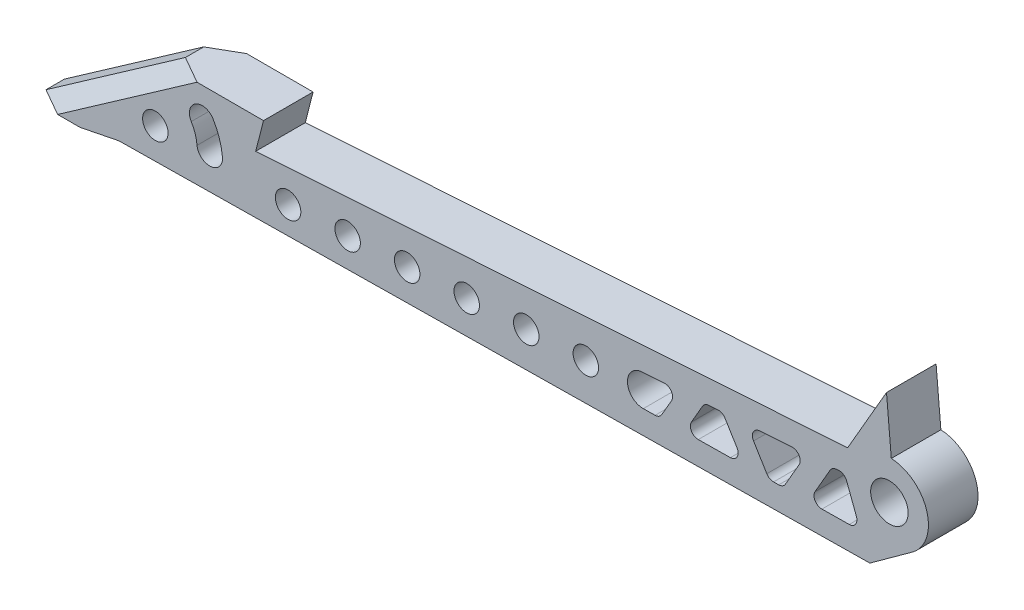
SolidWorks part; units mm, degrees
ref_plane "Front Plane" through (0, 0, 0) normal (0, 0, 1) x (1, 0, 0)
ref_plane "Top Plane" through (0, 0, 0) normal (0, 1, 0) x (1, 0, 0)
ref_plane "Right Plane" through (0, 0, 0) normal (1, 0, 0) x (0, 0, -1)
sketch "Sketch1" plane through (0, 0, 0) normal (0, 0, 1) x (1, 0, 0)
  line L0 (-207.3, -20.475) -> (-197.3, -18.475)
  line L1 (-207.3, -20.475) -> (-220, -20.475)
  line L2 (-220, -20.475) -> (-184.2963, 4.525)
  line L3 (-184.2963, 4.525) -> (-160.2963, 4.525)
  line L4 (-160.2963, 4.525) -> (-162.2963, -3.2821)
  line L5 (-63.3489, -2.738) -> (-11.4925, 0.6985)
  line L6 (-197.3, -18.475) -> (-5, -15.975)
  line L7 (-5, -15.975) -> (5.8689, -8.0967)
  line L8 (-7.1414, 7) -> (-162.2963, -3.2821)
  line L9 (-10.6917, 6.7647) -> (-0.7409, 24)
  line L10 (-11.4925, 0.6985) -> (-7.438, -10.0062)
  line L11 (-7.438, -10.0062) -> (-63.0324, -10.7289)
  line L12 (-0.7409, 24) -> (0.4849, 9.9882)
  line L13 (-0.4809, 25.4503) -> (7.4574, 39.2) construction
  line L14 (-154, -10.975) -> (-138.75, -10.2628)
  line L15 (-154, -17.9121) -> (-154, -2.7323) construction
  line L16 (-138.75, -10.2628) -> (-123.5, -9.5507)
  line L17 (-123.5, -9.5507) -> (-108.25, -8.8385)
  line L18 (-108.25, -8.8385) -> (-93, -8.1263)
  line L19 (-138.75, -10.2628) -> (-123.5, -9.5507)
  line L20 (-123.5, -9.5507) -> (-108.25, -8.8385)
  line L21 (-108.25, -8.8385) -> (-93, -8.1263)
  line L22 (-93, -8.1263) -> (-77.75, -7.4142)
  line L23 (-220, -20.475) -> (248.3161, -20.475) construction
  circle A0 centre (0, 0) radius 10
  circle A1 centre (0, 0) radius 4.8025
  arc A2 (-63.0324, -10.7289) -> (-63.3489, -2.738) centre (-63.0844, -6.7293) cw
  circle A3 centre (-154, -10.975) radius 3.2639
  circle A4 centre (-123.5, -9.5507) radius 3.2639
  circle A5 centre (-93, -8.1263) radius 3.2639
  circle A6 centre (-138.75, -10.2628) radius 3.2639
  circle A7 centre (-108.25, -8.8385) radius 3.2639
  circle A8 centre (-77.75, -7.4142) radius 3.2639
  point P0 (0, 0)
  point P3 (-180.2963, -4.475)
  point P42 (-172.5511, -3.4613)
  point P43 (-171.7203, -3.4613)
  point P44 (-170.2963, -3.8123)
  point P45 (0, 0)
  point P46 (-190, -11.126)
  dimension "D17" = 4
  dimension "D18" = 6.5278
  dimension "D8" = 20
  dimension "D22" = 9.605
  dimension "D1" = 12.7
  dimension "D2" = 35
  dimension "D3" = 220
  dimension "D4" = 24
  dimension "D5" = 2
  dimension "D6" = 25
  dimension "D7" = 2
  dimension "D9" = 5
  dimension "D10" = 6
  dimension "D11" = 6
  dimension "D12" = 70
  dimension "D13" = 10.5
  dimension "D14" = 1
  dimension "D15" = 10
  dimension "D16" = 35
  dimension "D19" = 66
  dimension "D20" = 127
  dimension "D21" = 7
  dimension "D23" = 24
  dimension "D24" = 0.7409
  dimension "D25" = 0.4849
  dimension "D26" = 10.6917
  dimension "D27" = 15.975
  dimension "D28" = 20.475
  dimension "D29" = 9.5
extrude "Boss-Extrude1" add sketch "Sketch1" along normal blind 12.7
sketch "Sketch2" plane through (0, 0, 12.7) normal (0, 0, 1) x (1, 0, 0)
  line L0 (-17.9421, 0.2711) -> (-24, -10.2215)
  line L1 (-33.9992, -10.3515) -> (-39.6248, -1.1658)
  line L2 (-33.9992, -10.3515) -> (-31.9101, -13.7626)
  line L3 (-24, -10.2215) -> (-25.5, -12.8196)
  line L4 (-17.9421, 0.2711) -> (-16.4421, 2.8692)
  line L5 (-39.6248, -1.1658) -> (-41.7139, 2.2453)
  line L6 (-50.6248, -1.8948) -> (-55.6699, -10.6332)
  line L7 (-55.6699, -10.6332) -> (-57.1699, -13.2313)
  line L8 (-50.6248, -1.8948) -> (-49.1248, 0.7033)
  line L9 (-28.9996, -10.2865) -> (-29.3793, 18.9221) construction
  line L10 (-7.438, -10.0062) -> (-63.0324, -10.7289) construction
  line L11 (-63.3489, -2.738) -> (-11.4925, 0.6985) construction
  point P4 (0, 0)
  point P5 (0, 0)
  point P19 (0, 0)
  point P20 (0, 0)
  point P23 (0, 0)
  point P24 (0, 0)
  point P25 (0, 0)
  point P26 (0, 0)
  point P29 (0, 0)
  point P30 (0, 0)
  point P31 (0, 0)
  dimension "D1" = 24
  dimension "D2" = 3
  dimension "D3" = 4
  dimension "D4" = 3
  dimension "D5" = 30.74
  dimension "D6" = 5
  dimension "D7" = 11
  dimension "D8" = 30.745
extrude "Extrude-Thin1" add sketch "Sketch2" against normal up to surface (12.7 mm away) thin up to face at (-74.4861, -7.4142, 0) thin type mid plane wall 5.5
fillet "Fillet1" radius 2 14 edges at (-11.4925, 0.6985, 6.35) (-47.323, -1.676, 6.35) (-42.7238, -1.3712, 6.35) (-53.9265, -2.1136, 6.35) (-14.6404, 0.4899, 6.35) (-36.5258, -0.9605, 6.35) (-21.2439, 0.0523, 6.35) (-52.4705, -10.5916, 6.35) (-37.1984, -10.3931, 6.35) (-58.8694, -10.6748, 6.35) (-20.8006, -10.1799, 6.35) (-7.438, -10.0062, 6.35) (-30.7999, -10.3099, 6.35) (-27.1994, -10.2631, 6.35)
sketch "Sketch3" plane through (0, 0, 12.7) normal (0, 0, 1) x (1, 0, 0)
  line L0 (-220, -20.475) -> (-184.2963, 4.525) construction
  line L1 (-220, -20.475) -> (-184.2963, 4.525) construction
  line L2 (-188, -10.475) -> (-174.0616, -9.1627) construction
  line L3 (-188, -10.475) -> (-176.0046, -3.2563) construction
  circle A0 centre (-188, -10.475) radius 3.2639
  arc A1 (-176.0046, -3.2563) -> (-174.0616, -9.1627) centre (-188, -10.475) cw construction
  arc A2 (-170.811, -8.8566) -> (-173.207, -1.5728) centre (-188, -10.475) ccw
  arc A3 (-177.3123, -9.4687) -> (-178.8021, -4.9398) centre (-188, -10.475) ccw
  arc A4 (-177.3123, -9.4687) -> (-170.811, -8.8566) centre (-174.0616, -9.1627) ccw
  arc A5 (-173.207, -1.5728) -> (-178.8021, -4.9398) centre (-176.0046, -3.2563) ccw
  point P7 (-174.7011, -6.1003)
  point P13 (0, 0)
  point P14 (-190.4436, -12.6036)
  point P15 (-179.2416, -1.4534)
  point P17 (-174.0217, -9.1589)
  point P18 (-178.0698, -2.0876)
  point P19 (-176.2764, -3.4199)
  point P20 (-174.0616, -9.1627)
  point P21 (-174.4618, -6.0216)
  point P22 (0, 0)
  dimension "D1" = 6.5278
  dimension "D5" = 3.265
  dimension "D2" = 32
  dimension "D3" = 10
  dimension "D4" = 14
  dimension "D6" = 1.3123
  dimension "D7" = 25.66
extrude "Cut-Extrude1" cut sketch "Sketch3" against normal through all
chamfer "Chamfer1" distance 4 angle 45 2 edges at (-202.1481, -7.975, 0) (-202.1481, -7.975, 12.7)
